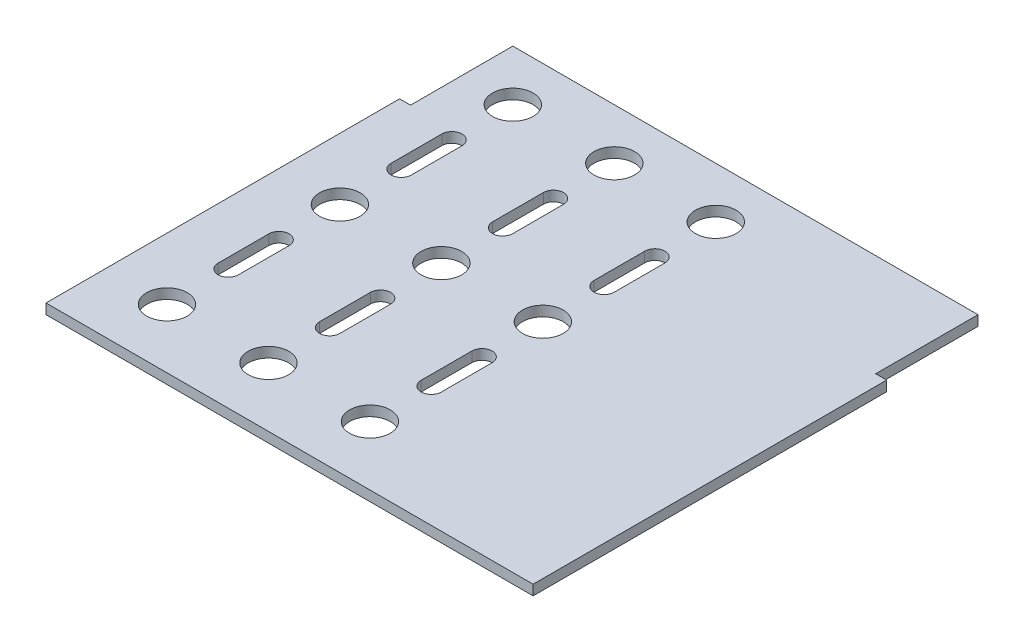
SolidWorks part; units mm, degrees
ref_plane "Front Plane" through (0, 0, 0) normal (0, 0, 1) x (1, 0, 0)
ref_plane "Top Plane" through (0, 0, 0) normal (0, 1, 0) x (1, 0, 0)
ref_plane "Right Plane" through (0, 0, 0) normal (1, 0, 0) x (0, 0, -1)
sketch "Sketch1" plane through (0, 0, 0) normal (0, 1, 0) x (1, 0, 0)
  line L1 (0, 0) -> (152.4, 0)
  line L2 (0, 0) -> (0, 142.621)
  line L3 (0, 142.621) -> (152.4, 142.621)
  line L4 (152.4, 0) -> (152.4, 142.621)
  dimension "D1" = 152.4
  dimension "D2" = 142.621
extrude "Boss-Extrude1" add sketch "Sketch1" along normal blind 3.175
sketch "Sketch2" plane through (0, 3.175, 0) normal (0, 1, 0) x (1, 0, 0)
  line L1 (0, 142.621) -> (3.429, 142.621)
  line L2 (0, 142.621) -> (0, 110.617)
  line L3 (0, 110.617) -> (3.429, 110.617)
  line L4 (3.429, 142.621) -> (3.429, 110.617)
  line L5 (152.4, 142.621) -> (148.971, 142.621)
  line L6 (152.4, 142.621) -> (152.4, 110.617)
  line L7 (152.4, 110.617) -> (148.971, 110.617)
  line L8 (148.971, 142.621) -> (148.971, 110.617)
  dimension "D1" = 3.429
  dimension "D2" = 32.004
extrude "Cut-Extrude1" cut sketch "Sketch2" against normal through all
sketch "Sketch3" plane through (0, 3.175, 0) normal (0, 1, 0) x (1, 0, 0)
  line L0 (19.304, 107.696) -> (19.304, 91.821) construction
  line L1 (22.479, 107.696) -> (22.479, 91.821)
  line L2 (16.129, 107.696) -> (16.129, 91.821)
  line L3 (3.429, 110.617) -> (3.429, 142.621) construction
  line L4 (148.971, 142.621) -> (3.429, 142.621) construction
  line L5 (51.054, 107.696) -> (51.054, 91.821) construction
  line L6 (54.229, 107.696) -> (54.229, 91.821)
  line L7 (47.879, 107.696) -> (47.879, 91.821)
  line L8 (82.804, 107.696) -> (82.804, 91.821) construction
  line L9 (85.979, 107.696) -> (85.979, 91.821)
  line L10 (79.629, 107.696) -> (79.629, 91.821)
  line L11 (19.304, 53.594) -> (19.304, 37.719) construction
  line L12 (22.479, 53.594) -> (22.479, 37.719)
  line L13 (16.129, 53.594) -> (16.129, 37.719)
  line L14 (51.054, 53.594) -> (51.054, 37.719) construction
  line L15 (54.229, 53.594) -> (54.229, 37.719)
  line L16 (47.879, 53.594) -> (47.879, 37.719)
  line L17 (82.804, 53.594) -> (82.804, 37.719) construction
  line L18 (85.979, 53.594) -> (85.979, 37.719)
  line L19 (79.629, 53.594) -> (79.629, 37.719)
  circle A0 centre (19.304, 126.746) radius 6.35
  arc A1 (22.479, 107.696) -> (16.129, 107.696) centre (19.304, 107.696) ccw
  arc A2 (16.129, 91.821) -> (22.479, 91.821) centre (19.304, 91.821) ccw
  circle A3 centre (51.054, 126.746) radius 6.35
  arc A4 (54.229, 107.696) -> (47.879, 107.696) centre (51.054, 107.696) ccw
  arc A5 (47.879, 91.821) -> (54.229, 91.821) centre (51.054, 91.821) ccw
  circle A6 centre (82.804, 126.746) radius 6.35
  arc A7 (85.979, 107.696) -> (79.629, 107.696) centre (82.804, 107.696) ccw
  arc A8 (79.629, 91.821) -> (85.979, 91.821) centre (82.804, 91.821) ccw
  circle A9 centre (19.304, 72.644) radius 6.35
  circle A10 centre (51.054, 72.644) radius 6.35
  circle A11 centre (82.804, 72.644) radius 6.35
  circle A12 centre (19.304, 18.542) radius 6.35
  circle A13 centre (51.054, 18.542) radius 6.35
  circle A14 centre (82.804, 18.542) radius 6.35
  arc A15 (22.479, 53.594) -> (16.129, 53.594) centre (19.304, 53.594) ccw
  arc A16 (16.129, 37.719) -> (22.479, 37.719) centre (19.304, 37.719) ccw
  arc A17 (54.229, 53.594) -> (47.879, 53.594) centre (51.054, 53.594) ccw
  arc A18 (47.879, 37.719) -> (54.229, 37.719) centre (51.054, 37.719) ccw
  arc A19 (85.979, 53.594) -> (79.629, 53.594) centre (82.804, 53.594) ccw
  arc A20 (79.629, 37.719) -> (85.979, 37.719) centre (82.804, 37.719) ccw
  point P4 (19.304, 99.7585)
  point P19 (51.054, 99.7585)
  point P28 (82.804, 99.7585)
  point P47 (19.304, 45.6565)
  point P54 (51.054, 45.6565)
  point P61 (82.804, 45.6565)
  dimension "D1" = 12.7
  dimension "D2" = 3.175
  dimension "D4" = 15.875
  dimension "D5" = 15.875
  dimension "D3" = 19.05
  dimension "D6" = 15.875
  dimension "D7" = 3
  dimension "D8" = 3
  dimension "D9" = 2
extrude "Cut-Extrude2" cut sketch "Sketch3" against normal up to next
